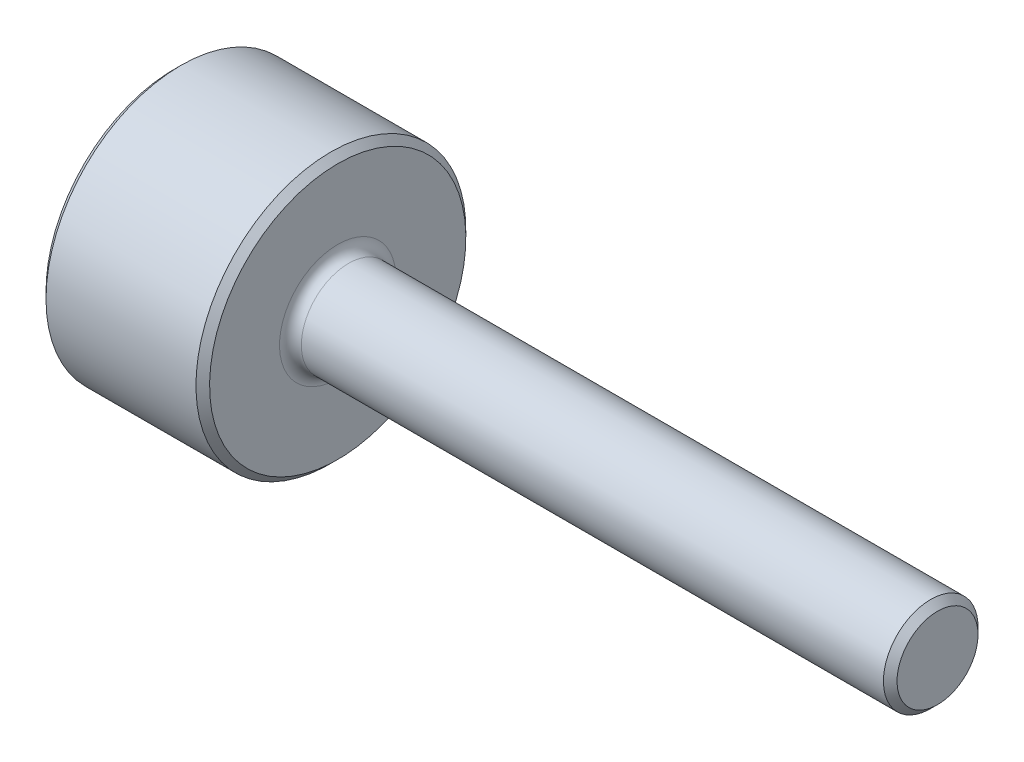
SolidWorks part; units mm, degrees
material "316 S/Steel"
ref_plane "Front Plane" through (0, 0, 0) normal (0, 0, 1) x (1, 0, 0)
ref_plane "Top Plane" through (0, 0, 0) normal (0, 1, 0) x (1, 0, 0)
ref_plane "Right Plane" through (0, 0, 0) normal (1, 0, 0) x (0, 0, -1)
sketch "Sketch1" plane through (0, 0, 0) normal (0, 0, 1) x (1, 0, 0)
  line L0 (0, 0) -> (0, 1.735)
  line L1 (0, 1.735) -> (-22, 1.735)
  line L2 (-22, 1.735) -> (-22, 4.95)
  line L3 (-22, 4.95) -> (-28, 4.95)
  line L4 (-28, 4.95) -> (-28, 0)
  line L5 (0, 0) -> (-28, 0) construction
  line L6 (0, 0) -> (-28, 0)
  dimension "D1" = 28
  dimension "D2" = 6
  dimension "D3" = 9.9
  dimension "D4" = 3.47
revolve "Revolve1" add sketch "Sketch1" angle 360 about L5
chamfer "Chamfer1" distance 0.25 angle 45 3 edges at (0, 1.735, 0) (-22, 4.95, 0) (-28, 4.95, 0)
fillet "Fillet1" radius 0.4 1 edges at (-22, 1.735, 0)
